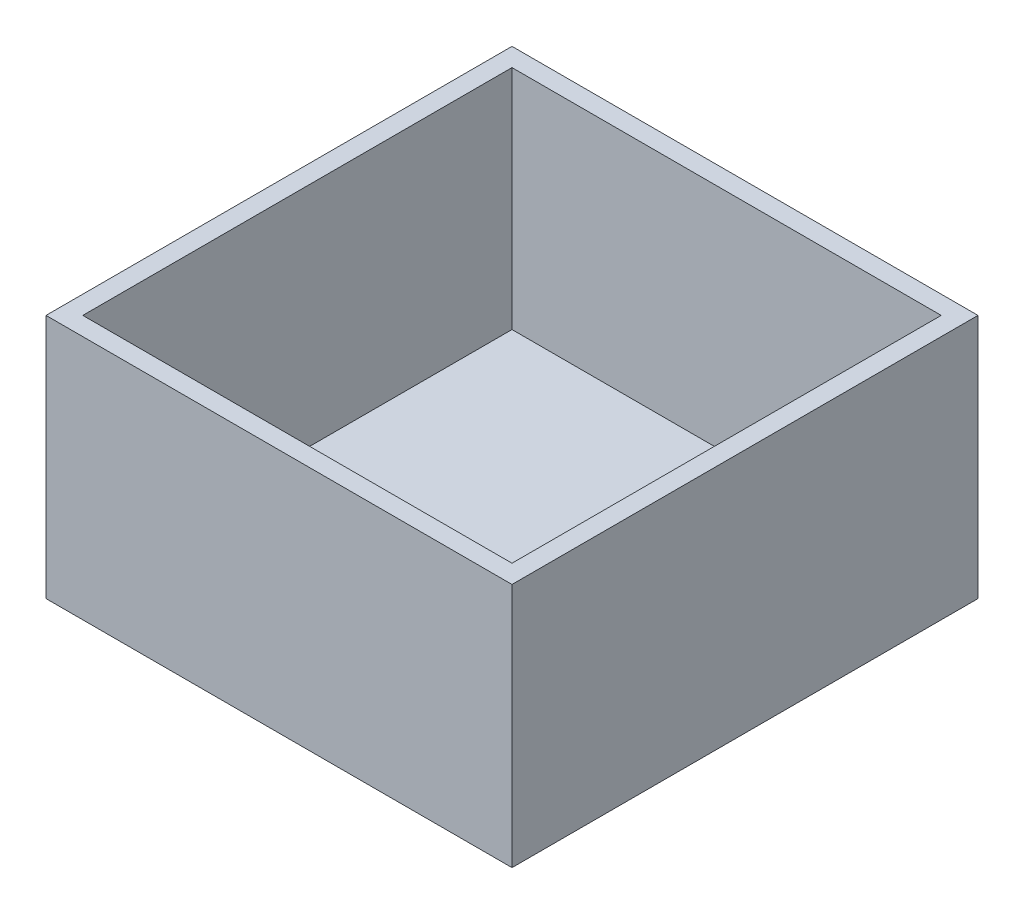
SolidWorks part; units mm, degrees
ref_plane "Front Plane" through (0, 0, 0) normal (0, 0, 1) x (1, 0, 0)
ref_plane "Top Plane" through (0, 0, 0) normal (0, 1, 0) x (1, 0, 0)
ref_plane "Right Plane" through (0, 0, 0) normal (1, 0, 0) x (0, 0, -1)
sketch "Sketch1" plane through (0, 0, 0) normal (0, 1, 0) x (1, 0, 0)
  line L0 (-3, -3) -> (-3, 73)
  line L1 (0, 0) -> (70, 0)
  line L2 (0, 0) -> (0, 70)
  line L3 (0, 70) -> (70, 70)
  line L4 (70, 0) -> (70, 70)
  line L5 (-3, 73) -> (73, 73)
  line L6 (73, -3) -> (73, 73)
  line L7 (-3, -3) -> (73, -3)
  dimension "D1" = 70
  dimension "D2" = 70
  dimension "D3" = 3
extrude "Boss-Extrude1" add sketch "Sketch1" along normal blind 40
sketch "Sketch2" plane through (0, 0, 0) normal (0, -1, 0) x (1, 0, 0)
  line L1 (70, -70) -> (0, -70)
  line L2 (70, -70) -> (70, 0)
  line L3 (70, 0) -> (0, 0)
  line L4 (0, -70) -> (0, 0)
extrude "Boss-Extrude2" add sketch "Sketch2" against normal blind 3
